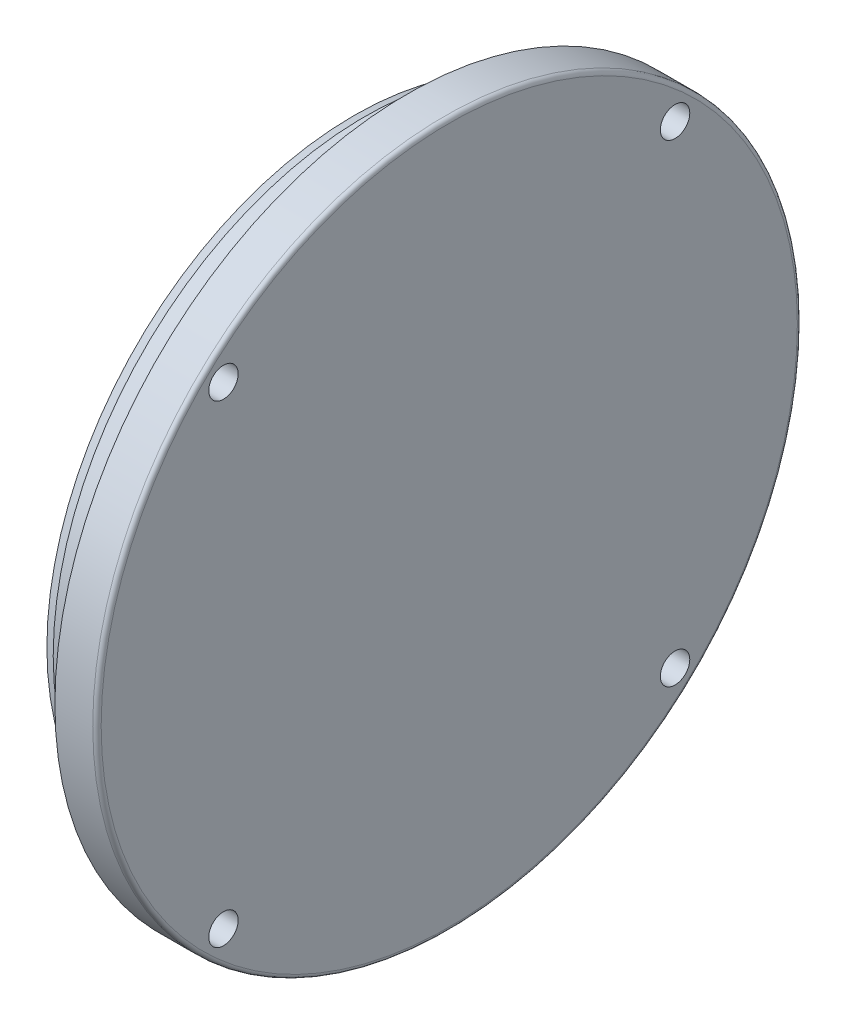
SolidWorks part; units mm, degrees
ref_plane "Front" through (0, 0, 0) normal (0, 0, 1) x (1, 0, 0)
ref_plane "Top" through (0, 0, 0) normal (0, 1, 0) x (1, 0, 0)
ref_plane "Right" through (0, 0, 0) normal (1, 0, 0) x (0, 0, -1)
sketch "Çizim1" plane through (0, 0, 0) normal (0, 0, 1) x (1, 0, 0)
  line L0 (0, 0) -> (45.3, 0) construction
  line L1 (48.1633, 0) -> (48.1633, 55.2041) construction
  line L2 (0, 0) -> (0, 55.2041) construction
  line L3 (0, 31) -> (5, 31)
  line L4 (0, 31) -> (0, 146)
  line L5 (5, 148) -> (25.3, 148)
  line L6 (25.3, 31) -> (25.3, 16)
  line L7 (25.3, 16) -> (35.3, 16)
  line L8 (45.3, 0) -> (45.3, 161)
  line L9 (45.3, 161) -> (45.3, 167.5)
  line L10 (45.3, 167.5) -> (25.3, 167.5)
  line L11 (25.3, 167.5) -> (25.3, 148)
  line L12 (7.3, 31) -> (25.3, 31)
  line L13 (5, 32.75) -> (7.3, 32.75)
  line L14 (5, 32.75) -> (5, 31)
  line L16 (7.3, 32.75) -> (7.3, 31)
  line L17 (0, 146) -> (5, 148)
  line L18 (35.3, 16) -> (35.3, 0)
  line L19 (35.3, 0) -> (45.3, 0)
  point P8 (0, 148)
  dimension "D1" = 31
  dimension "D2" = 25.3
  dimension "D3" = 148
  dimension "D4" = 20
  dimension "D5" = 32
  dimension "D6" = 20
  dimension "D7" = 167.5
  dimension "D8" = 5
  dimension "D9" = 2.3
  dimension "D10" = 32.75
  dimension "D11" = 5
  dimension "D12" = 2
  dimension "D13" = 10
revolve "Döndür1" add sketch "Çizim1" angle 360 about L0
sketch "Çizim2" plane through (45.3, 0, 0) normal (1, 0, 0) x (0, 0, -1)
  line L1 (107.3499, -112.5) -> (-107.3499, -112.5) construction
  line L2 (107.3499, -112.5) -> (107.3499, 112.5) construction
  line L3 (107.3499, 112.5) -> (-107.3499, 112.5) construction
  line L4 (-107.3499, -112.5) -> (-107.3499, 112.5) construction
  line L5 (107.3499, -112.5) -> (-107.3499, 112.5) construction
  line L6 (107.3499, 112.5) -> (-107.3499, -112.5) construction
  circle A0 centre (0, 0) radius 155.5 construction
  circle A1 centre (-107.3499, 112.5) radius 4
  circle A2 centre (107.3499, 112.5) radius 4
  circle A3 centre (107.3499, -112.5) radius 4
  circle A4 centre (-107.3499, -112.5) radius 4
  dimension "D1" = 311
  dimension "D3" = 8
  dimension "D2" = 225
extrude "Kes-Ekstrüzyon1" cut sketch "Çizim2" against normal up to surface (20 mm away) up to face at (25.3, 0, 148)
sketch "Çizim3" plane through (45.3, 0, 0) normal (1, 0, 0) x (0, 0, -1)
  circle A0 centre (-107.3499, 112.5) radius 7
  circle A1 centre (107.3499, 112.5) radius 7
  circle A2 centre (107.3499, -112.5) radius 7
  circle A3 centre (-107.3499, -112.5) radius 7
  dimension "D1" = 14
extrude "Kes-Ekstrüzyon2" cut sketch "Çizim3" against normal blind 10
fillet "Radyus1" radius 2 1 edges at (45.3, 0, 167.5)
